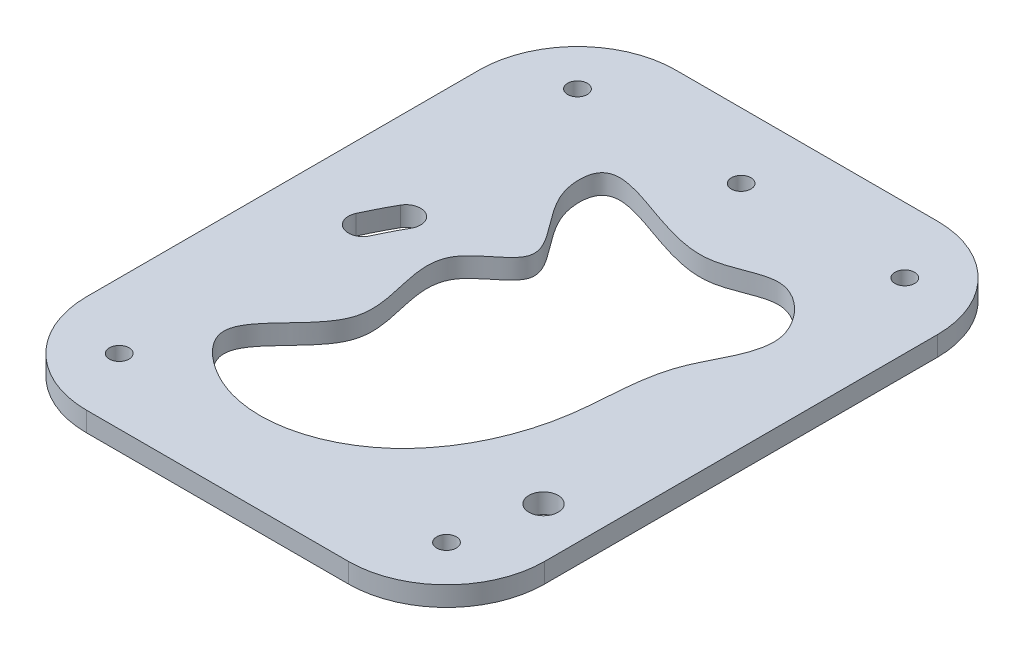
SolidWorks part; units mm, degrees
material "聚脂树脂"
ref_plane "前视基准面" through (0, 0, 0) normal (0, 0, 1) x (1, 0, 0)
ref_plane "上视基准面" through (0, 0, 0) normal (0, 1, 0) x (1, 0, 0)
ref_plane "右视基准面" through (0, 0, 0) normal (1, 0, 0) x (0, 0, -1)
sketch "草图1" plane through (0, 0, 0) normal (0, 1, 0) x (1, 0, 0)
  line L0 (-31.0238, -43.8726) -> (8.9762, -43.8726)
  line L1 (23.9762, -28.8726) -> (23.9762, 31.1274)
  line L2 (8.9762, 46.1274) -> (-31.0238, 46.1274)
  line L3 (-46.0238, 31.1274) -> (-46.0238, -28.8726)
  circle A0 centre (-11.0238, 36.1274) radius 1.5
  circle A1 centre (-36.0238, 36.1274) radius 1.5
  circle A2 centre (13.9762, 36.1274) radius 1.5
  circle A3 centre (13.9762, -33.8726) radius 1.5
  circle A4 centre (-36.0238, -33.8726) radius 1.5
  circle A5 centre (16.2754, -21.3567) radius 2.237
  arc A6 (-36.4753, 2.7237) -> (-32.4052, 0.8658) centre (-34.4403, 1.7948) ccw
  arc A7 (-34.1758, 7.2296) -> (-36.4753, 2.7237) centre (16.2754, -21.3567) ccw
  arc A8 (-30.2832, 5.024) -> (-34.1758, 7.2296) centre (-32.2295, 6.1268) ccw
  arc A9 (-30.2832, 5.024) -> (-32.4052, 0.8658) centre (16.2754, -21.3567) ccw
  arc A10 (8.9762, -43.8726) -> (23.9762, -28.8726) centre (8.9762, -28.8726) ccw
  arc A11 (23.9762, 31.1274) -> (8.9762, 46.1274) centre (8.9762, 31.1274) ccw
  arc A12 (-31.0238, 46.1274) -> (-46.0238, 31.1274) centre (-31.0238, 31.1274) ccw
  arc A13 (-46.0238, -28.8726) -> (-31.0238, -43.8726) centre (-31.0238, -28.8726) ccw
  spline S0 degree 3 poles (6.5454, 6.7372) (15.4684, 17.9919) (5.5325, 28.7063) (-6.0478, 19.0235) (-24.1677, 32.703) (-23.8805, 18.2257) (-13.1788, 10.9302) (-28.3376, 3.5503) (-16.938, -11.9261) (-35.1793, -21.2686) (-21.7913, -33.6256) (-1.6632, -29.7412) (7.7871, -9.8767) (6.5454, 6.7372) (15.4684, 17.9919) (5.5325, 28.7063) knots -0.286762 -0.156179 -0.069194 0 0.054917 0.11147 0.226545 0.252267 0.325912 0.370317 0.460933 0.545778 0.589931 0.713238 0.843821 0.930806 1 1.054917 1.11147 1.226545 only from (12.3197, 18.9841) to (12.3197, 18.9841)
extrude "凸台-拉伸1" add sketch "草图1" along normal blind 3
